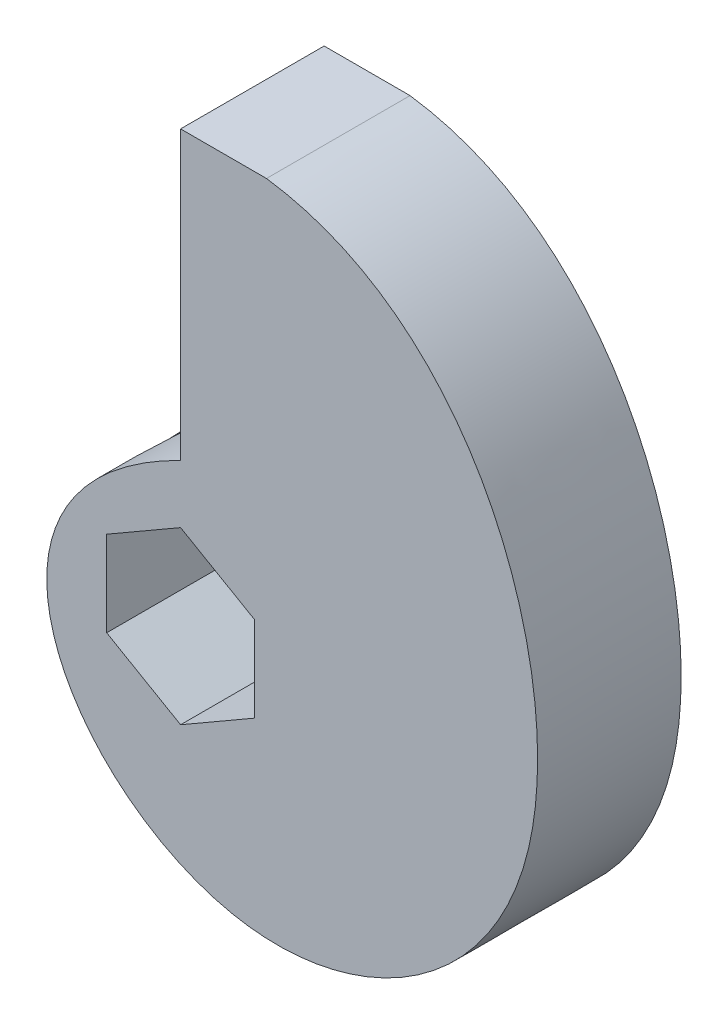
SolidWorks part; units mm, degrees
material "ABS"
ref_plane "Front Plane" through (0, 0, 0) normal (0, 0, 1) x (1, 0, 0)
ref_plane "Top Plane" through (0, 0, 0) normal (0, 1, 0) x (1, 0, 0)
ref_plane "Right Plane" through (0, 0, 0) normal (1, 0, 0) x (0, 0, -1)
sketch "Sketch1" plane through (0, 0, 0) normal (0, 0, 1) x (1, 0, 0)
  line L0 (0, 0) -> (0, 38.1)
  line L1 (-38.1, 38.1) -> (38.1, 38.1)
  line L2 (-38.1, 38.1) -> (-38.1, -38.1)
  line L3 (-38.1, -38.1) -> (38.1, -38.1)
  line L4 (38.1, 38.1) -> (38.1, -38.1)
  line L5 (-38.1, 38.1) -> (38.1, -38.1) construction
  line L6 (-38.1, -38.1) -> (38.1, 38.1) construction
  circle A0 centre (0, 0) radius 3.175
  spline S0 degree 3 poles (0, 38.1) (24.1321, 41.1545) (42.8064, -5.7788) (-0.4683, -31.5474) (-21.773, 1.9493) (0, 12.7) knots 0 0 0 0 0.338031 0.620421 1 1 1 1
  point P0 (0, 0)
  dimension "D4" = 6.35
  dimension "D1" = 76.2
  dimension "D2" = 76.2
  dimension "D3" = 25.4
extrude "Boss-Extrude1" add sketch "Sketch1" along normal blind 12.7
sketch "Sketch2" plane through (0, 0, 12.7) normal (0, 0, 1) x (1, 0, 0)
  line L1 (6.5405, -3.7762) -> (6.5405, 3.7762)
  line L2 (6.5405, 3.7762) -> (0, 7.5523)
  line L3 (0, 7.5523) -> (-6.5405, 3.7762)
  line L4 (-6.5405, 3.7762) -> (-6.5405, -3.7762)
  line L5 (-6.5405, -3.7762) -> (0, -7.5523)
  line L6 (0, -7.5523) -> (6.5405, -3.7762)
  circle A0 centre (0, 0) radius 6.5405 construction
  dimension "D1" = 13.081
extrude "Cut-Extrude1" cut sketch "Sketch2" against normal through all
